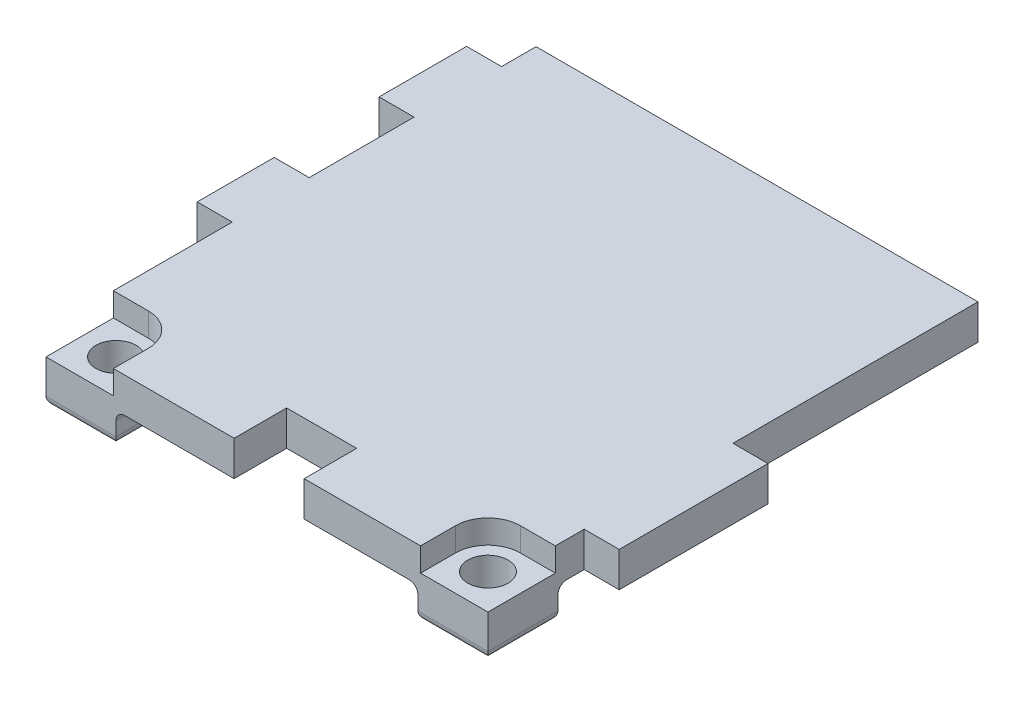
SolidWorks part; units mm, degrees
material "玻璃"
ref_plane "前视基准面" through (0, 0, 0) normal (0, 0, 1) x (1, 0, 0)
ref_plane "上视基准面" through (0, 0, 0) normal (0, 1, 0) x (1, 0, 0)
ref_plane "右视基准面" through (0, 0, 0) normal (1, 0, 0) x (0, 0, -1)
sketch "草图1" plane through (0, 0, 0) normal (0, 1, 0) x (1, 0, 0)
  line L1 (12.625, -13) -> (-12.625, -13)
  line L2 (12.625, -13) -> (12.625, 13)
  line L3 (12.625, 13) -> (-12.625, 13)
  line L4 (-12.625, -13) -> (-12.625, 13)
  line L5 (12.625, -13) -> (-12.625, 13) construction
  line L6 (12.625, 13) -> (-12.625, -13) construction
  point P0 (0, 0)
extrude "凸台-拉伸1" add sketch "草图1" along normal blind 2
sketch "草图3" plane through (0, 0, 0) normal (0, 1, 0) x (1, 0, 0)
  line L1 (-12.625, -13) -> (-8.625, -13)
  line L2 (-12.625, -13) -> (-12.625, -9)
  line L3 (-12.625, -9) -> (-8.625, -9)
  line L4 (-8.625, -13) -> (-8.625, -9)
  line L9 (12.625, -13) -> (8.625, -13)
  line L10 (12.625, -13) -> (12.625, -9)
  line L11 (12.625, -9) -> (8.625, -9)
  line L12 (8.625, -13) -> (8.625, -9)
  point P10 (0, 0)
extrude "凸台-拉伸2" add sketch "草图3" against normal blind 1.8
sketch "草图4" plane through (0, 0, 0) normal (0, 1, 0) x (1, 0, 0)
  line L0 (-12.625, 13) -> (-12.625, -13) construction
  line L2 (-12.625, -13) -> (12.625, -13) construction
  line L3 (0, 0) -> (0, -9.5972) construction
  circle A0 centre (-10.625, -11) radius 1.15
  circle A1 centre (10.625, -11) radius 1.15
  dimension "D1" = 2
  dimension "D2" = 2
extrude "切除-拉伸2" cut sketch "草图4" against normal blind 1.8 and the other way blind 2
sketch "草图5" plane through (0, 2, 0) normal (0, 1, 0) x (1, 0, 0)
  line L0 (-12.625, 13) -> (-12.625, -13) construction
  line L4 (-12.625, -13) -> (12.625, -13) construction
  line L5 (0, 0) -> (0, -10.1705) construction
  circle A0 centre (-10.625, -11) radius 1.85
  circle A3 centre (10.625, -11) radius 1.85
  dimension "D1" = 2
  dimension "D2" = 2
extrude "切除-拉伸3" cut sketch "草图5" against normal blind 1.35
sketch "草图7" plane through (0, 0, -13) normal (0, 0, -1) x (-1, 0, 0)
  line L0 (-12.625, 2) -> (-12.625, 0)
  line L1 (-12.625, 0) -> (12.625, 0)
  line L2 (12.625, 0) -> (12.625, 2)
  line L3 (12.625, 2) -> (-12.625, 2)
extrude "凸台-拉伸4" add sketch "草图7" along normal blind 2
fillet "圆角3" radius 0.5 12 edges at (-8.625, 0, 11) (-10.625, 0, 9) (10.625, 0, 9) (8.625, 0, 11) (-10.625, -1.8, 9) (-12.625, -1.8, 11) (-8.625, -1.8, 11) (-10.625, -1.8, 13) (8.625, -1.8, 11) (10.625, -1.8, 9) (12.625, -1.8, 11) (10.625, -1.8, 13)
sketch "草图8" plane through (12.625, 0, 0) normal (1, 0, 0) x (0, 0, -1)
  line L0 (-13, 2) -> (-7.5, 2) construction
  line L1 (-13, 2) -> (15, 2) construction
  line L6 (1, 2) -> (-7.5, 2)
  line L7 (-7.5, 2) -> (-7.5, 0)
  line L8 (-8.5, 0) -> (15, 0) construction
  line L9 (-7.5, 0) -> (1, 0)
  line L10 (1, 0) -> (1, 2)
  point P10 (-3.25, 2)
extrude "凸台-拉伸5" add sketch "草图8" along normal blind 2
sketch "草图9" plane through (-12.625, 0, 0) normal (-1, 0, 0) x (0, 0, 1)
  line L0 (13, 2) -> (-7.5307, 2) construction
  line L1 (-15, 2) -> (13, 2) construction
  line L3 (-15, 0) -> (8.5, 0) construction
  line L4 (-8.0307, 0) -> (-13.0307, 0)
  line L7 (-8.0307, 0) -> (-8.0307, 2)
  line L8 (-8.0307, 2) -> (-13.0307, 2)
  line L9 (-13.0307, 2) -> (-13.0307, 0)
  point P10 (-10.5307, 0)
extrude "凸台-拉伸6" add sketch "草图9" along normal blind 2
sketch "草图10" plane through (-12.625, 0, 0) normal (-1, 0, 0) x (0, 0, 1)
  line L0 (13, 2) -> (2.86, 2) construction
  line L1 (-8.0307, 2) -> (13, 2) construction
  line L4 (-8.0307, 0) -> (8.5, 0) construction
  line L5 (-2.04, 0) -> (2.36, 0)
  line L7 (-2.04, 0) -> (-2.04, 2)
  line L8 (2.36, 0) -> (2.36, 2)
  line L9 (2.36, 2) -> (-2.04, 2)
  point P11 (0.16, 0)
extrude "凸台-拉伸7" add sketch "草图10" along normal blind 2
sketch "草图11" plane through (0, 2, 0) normal (0, 1, 0) x (1, 0, 0)
  line L0 (12.625, -13) -> (0.125, -13) construction
  line L1 (-12.625, -13) -> (12.625, -13) construction
  line L2 (0.125, -13) -> (0.125, -11.5) construction
  line L4 (2.125, -13) -> (-1.875, -13)
  line L5 (2.125, -13) -> (2.125, -10)
  line L6 (2.125, -10) -> (-1.875, -10)
  line L7 (-1.875, -13) -> (-1.875, -10)
  line L8 (2.125, -13) -> (-1.875, -10) construction
  line L9 (2.125, -10) -> (-1.875, -13) construction
extrude "切除-拉伸4" cut sketch "草图11" against normal blind 2
sketch "草图12" plane through (0, 2, 0) normal (0, 1, 0) x (1, 0, 0)
  line L0 (-10.625, -9.15) -> (-12.625, -9.15)
  line L1 (-12.625, -2.36) -> (-12.625, -13) construction
  line L2 (-12.625, -9.15) -> (-12.625, -13)
  line L3 (-12.625, -13) -> (-8.775, -13)
  line L4 (-12.625, -13) -> (-1.875, -13) construction
  line L5 (-8.775, -13) -> (-8.775, -11)
  line L6 (-8.775, -11) -> (-10.625, -9.15)
  line L7 (0, 0) -> (0, -7.3179) construction
  line L8 (8.775, -11) -> (10.625, -9.15)
  line L9 (8.775, -13) -> (8.775, -11)
  line L10 (12.625, -13) -> (8.775, -13)
  line L11 (12.625, -9.15) -> (12.625, -13)
  line L12 (10.625, -9.15) -> (12.625, -9.15)
  circle A0 centre (-10.625, -11) radius 1.85 construction
extrude "切除-拉伸5" cut sketch "草图12" against normal blind 1.35
